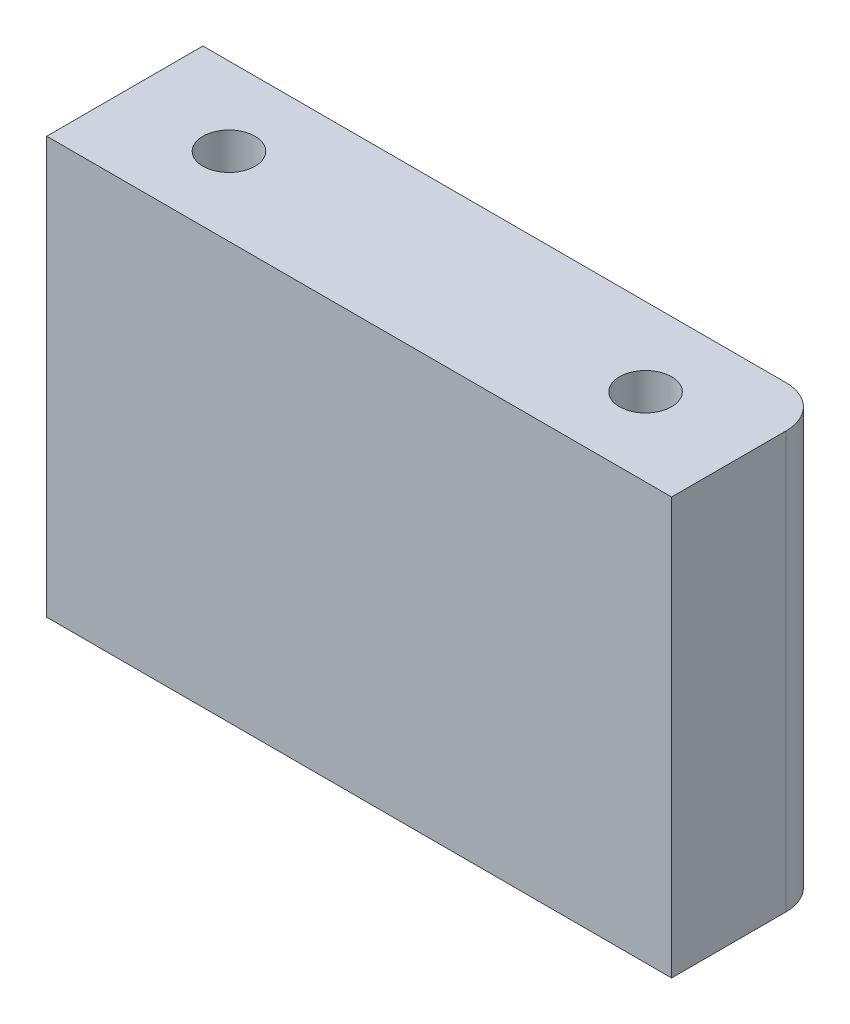
SolidWorks part; units mm, degrees
ref_plane "Front Plane" through (0, 0, 0) normal (0, 0, 1) x (1, 0, 0)
ref_plane "Top Plane" through (0, 0, 0) normal (0, 1, 0) x (1, 0, 0)
ref_plane "Right Plane" through (0, 0, 0) normal (1, 0, 0) x (0, 0, -1)
sketch "Sketch1" plane through (0, 0, 0) normal (0, 0, 1) x (1, 0, 0)
  line L1 (0, 0) -> (38.1, 0)
  line L2 (0, 0) -> (0, 25.4)
  line L3 (0, 25.4) -> (38.1, 25.4)
  line L4 (38.1, 0) -> (38.1, 25.4)
  dimension "D1" = 25.4
  dimension "D2" = 38.1
extrude "Boss-Extrude1" add sketch "Sketch1" along normal blind 9.525
sketch "Sketch2" plane through (0, 0, 0) normal (0, -1, 0) x (1, 0, 0)
  line L0 (0, 4.7625) -> (38.1, 4.7625) construction
  line L1 (0, 9.525) -> (0, 0) construction
  line L2 (38.1, 9.525) -> (38.1, 0) construction
  line L3 (19.05, 9.525) -> (19.05, 0) construction
  line L4 (0, 9.525) -> (38.1, 9.525) construction
  line L5 (0, 0) -> (38.1, 0) construction
  circle A0 centre (6.35, 4.7625) radius 1.5875
  circle A1 centre (31.75, 4.7625) radius 1.5875
  dimension "D1" = 3.175
  dimension "D2" = 6.35
extrude "Cut-Extrude1" cut sketch "Sketch2" against normal through all
fillet "Fillet1" radius 2.54 1 edges at (38.1, 12.7, 0)
